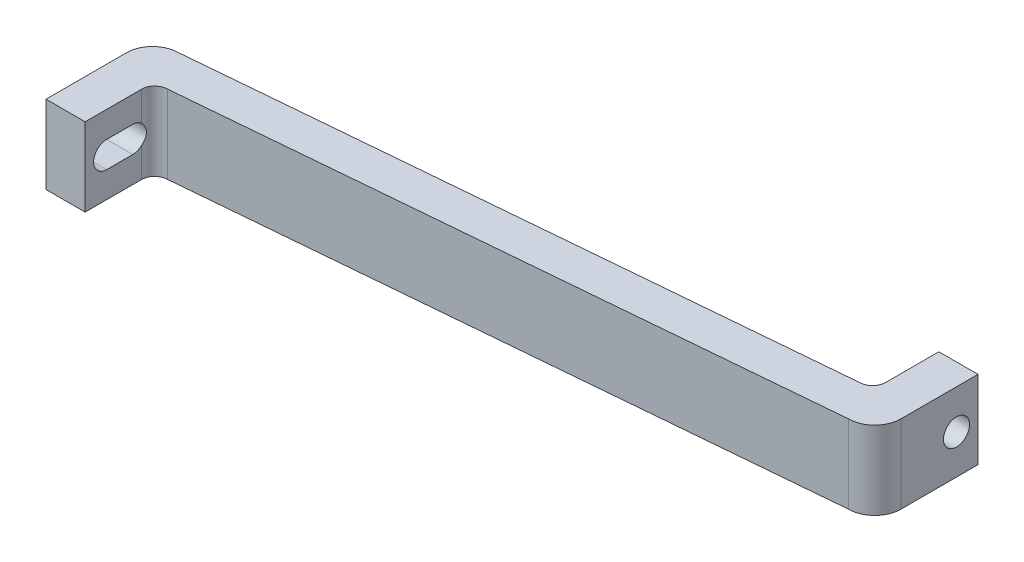
SolidWorks part; units mm, degrees
ref_plane "Front Plane" through (0, 0, 0) normal (0, 0, 1) x (1, 0, 0)
ref_plane "Top Plane" through (0, 0, 0) normal (0, 1, 0) x (1, 0, 0)
ref_plane "Right Plane" through (0, 0, 0) normal (1, 0, 0) x (0, 0, -1)
sketch "Sketch1" plane through (0, 0, 0) normal (0, 1, 0) x (1, 0, 0)
  line L0 (0, 0) -> (3, 0)
  line L1 (3, 0) -> (3, 4.33)
  line L3 (54, 10.1564) -> (54, 17.46)
  line L4 (54, 17.46) -> (51, 17.46)
  line L5 (51, 17.46) -> (51, 13.38)
  line L7 (0, 6.17) -> (0, 0)
  line L8 (4, 5.33) -> (52, 9.54)
  line L9 (2, 8.17) -> (50, 12.38)
  arc A0 (4, 5.33) -> (3, 4.33) centre (4, 4.33) ccw
  arc A1 (50, 12.38) -> (51, 13.38) centre (50, 13.38) ccw
  arc A2 (2, 8.17) -> (0, 6.17) centre (2, 6.17) ccw
  arc A3 (52, 9.54) -> (54, 11.54) centre (52, 11.54) ccw
  point P16 (52.5, 17.46)
  dimension "D6" = 2
  dimension "D9" = 2
  dimension "D10" = 4
  dimension "D11" = 4
  dimension "D1" = 3
  dimension "D2" = 3
  dimension "D3" = 1
  dimension "D4" = 1
  dimension "D5" = 54
  dimension "D7" = 4.33
  dimension "D8" = 4.08
  dimension "D12" = 2
  dimension "D13" = 2
  dimension "D14" = 6.17
  dimension "D15" = 5.92
  dimension "D16" = 17.46
extrude "Boss-Extrude1" add sketch "Sketch1" along normal blind 6 contours L8 A3 L3 L4 L5 A1 L9 A2 L7 L0 L1 A0
sketch "Sketch3" plane through (0, 0, 0) normal (1, 0, 0) x (0, 0, -1)
  line L0 (1.65, 4) -> (3.65, 4)
  line L1 (1.65, 2) -> (3.65, 2)
  line L2 (0, 6) -> (4.33, 6) construction
  line L3 (11.54, 6) -> (17.46, 6) construction
  line L4 (0, 6) -> (0, 0) construction
  circle A0 centre (15.81, 3) radius 1
  arc A1 (3.65, 2) -> (3.65, 4) centre (3.65, 3) ccw
  arc A2 (1.65, 4) -> (1.65, 2) centre (1.65, 3) ccw
  point P15 (0, 0)
  point P16 (0, 0)
  dimension "D1" = 1
  dimension "D2" = 1
  dimension "D3" = 2
  dimension "D4" = 12.16
  dimension "D5" = 2
  dimension "D6" = 3
  dimension "D7" = 3
  dimension "D8" = 1.65
extrude "Cut-Extrude1" cut sketch "Sketch3" along normal blind 59
